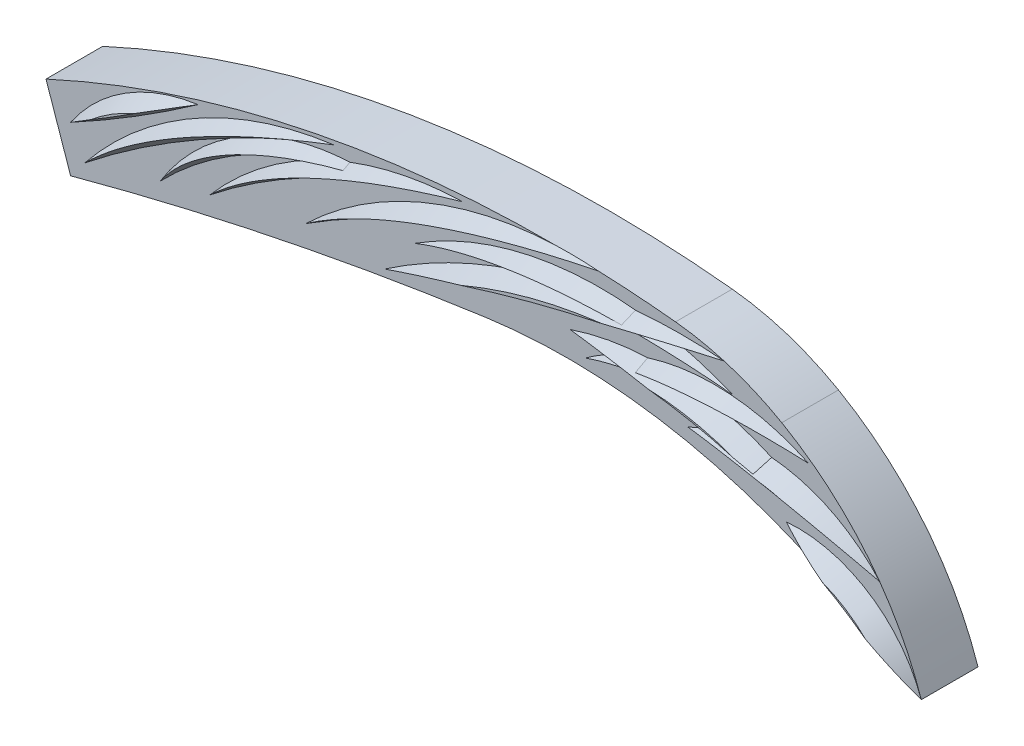
SolidWorks part; units mm, degrees
ref_plane "Plano frontal" through (0, 0, 0) normal (0, 0, 1) x (1, 0, 0)
ref_plane "Plano superior" through (0, 0, 0) normal (0, 1, 0) x (1, 0, 0)
ref_plane "Plano direito" through (0, 0, 0) normal (1, 0, 0) x (0, 0, -1)
sketch "Esboço4" plane through (0, 0, 0) normal (0, 0, 1) x (1, 0, 0)
  line L0 (0, 0) -> (-1.3028, 3.7819)
  arc A0 (-1.3028, 3.7819) -> (32, 9.3098) centre (25.4471, -54.2922) cw
  arc A1 (32, 9.3098) -> (37.6194, 7.5) centre (30.5413, -4.8482) cw
  arc A2 (45, -1.5) -> (22, 4.5) centre (26.2802, -26.176) ccw
  arc A3 (22, 4.5) -> (0, 0) centre (46.5941, -171.7657) ccw
  arc A4 (37.6194, 7.5) -> (45, -1.5) centre (29.4784, -6.7025) cw
  point P11 (29.4092, 8.7234)
  point P12 (34.2907, 7.7261)
  point P13 (25.5217, -13.5843)
  point P14 (23.8182, 4.8545)
  point P15 (0, 0)
  point P16 (34.6139, 7.3339)
  point P17 (21.2872, 5.0611)
  point P18 (22.1653, 4.4929)
  point P19 (26.8658, 8.8835)
  point P21 (28.2156, 8.9352)
  point P22 (34.0974, 9.1934)
  point P23 (30.2233, 9.71)
  point P24 (32.2034, 8.9868)
  point P25 (0, 0)
  point P26 (37.9197, 7.4372)
  point P27 (32, 9.3098)
  dimension "D9" = 63.9386
  dimension "D10" = 177.9732
  dimension "D11" = 14.233
  dimension "D12" = 16.3702
  dimension "D1" = 45
  dimension "D2" = 4
  dimension "D3" = 1.5
  dimension "D4" = 4.5
  dimension "D5" = 7.5
  dimension "D6" = 9.3098
  dimension "D7" = 22
  dimension "D8" = 32
extrude "Ressalto-extrusão2" add sketch "Esboço4" along normal blind 3
sketch "Esboço5" plane through (0, 0, 3) normal (0, 0, 1) x (1, 0, 0)
  arc A0 (0, 2.4508) -> (6.7381, 6.6316) centre (13.2084, -11.3167) cw
  arc A1 (0.7461, 0.9643) -> (13.9315, 8.3798) centre (20.9726, -19.5698) cw
  arc A2 (7.3646, 2.8065) -> (20.7523, 9.1823) centre (23.619, -14.0807) cw
  arc A3 (12.444, 4.0347) -> (27.9188, 9.5987) centre (29.3908, -18.7968) cw
  arc A4 (4.7377, 2.1242) -> (16.6099, 7.958) centre (16.2768, -6.3616) cw
  arc A5 (16.6099, 4.0347) -> (34.58, 8.7997) centre (36.2409, -33.7309) cw
  arc A6 (18.2133, 6.0134) -> (35.0324, 7.4803) centre (28.4248, -13.9131) cw
  arc A7 (27.2199, 5.2628) -> (39.0368, 6.345) centre (34.4616, -8.7549) cw
  arc A8 (32.6443, 4.8193) -> (42.8038, 2.8065) centre (35.7795, -6.0018) cw
  arc A9 (37.864, 3.0794) -> (45, -1.5) centre (36.488, -6.9145) cw
  arc A10 (32, 9.3098) -> (-1.3028, 3.7819) centre (25.4471, -54.2922) ccw construction
  arc A11 (37.6194, 7.5) -> (32, 9.3098) centre (30.5413, -4.8482) ccw construction
  arc A12 (45, -1.5) -> (37.6194, 7.5) centre (29.4784, -6.7025) ccw construction
  point P30 (6.7381, 6.6316)
  point P31 (13.9315, 8.3798)
  point P32 (20.7523, 9.1823)
  point P33 (27.9188, 9.5987)
  point P37 (34.58, 8.7997)
  point P41 (39.0368, 6.345)
  point P42 (42.8038, 2.8065)
  point P46 (45, -1.5)
sketch "Esboço6" plane through (0, 0, 3) normal (0, 0, 1) x (1, 0, 0)
  arc A0 (0, 2.4508) -> (6.7381, 6.6316) centre (8.079, -3.0498) cw
  arc A1 (0, 2.4508) -> (6.7381, 6.6316) centre (-31.6061, 60.9098) ccw
  arc A2 (6.7381, 6.6316) -> (0, 2.4508) centre (13.2084, -11.3167) ccw construction
  dimension "D1" = 9.729
  dimension "D2" = 85
extrude "Ressalto-extrusão5" add sketch "Esboço6" along normal blind 1 draft 23
sketch "Esboço7" plane through (0, 0, 3) normal (0, 0, 1) x (1, 0, 0)
  arc A0 (0.7461, 0.9643) -> (13.9315, 8.3798) centre (16.5557, -11.7163) cw
  arc A1 (0.7461, 0.9643) -> (13.9315, 8.3798) centre (30.5272, -36.5584) cw
  arc A2 (13.9315, 8.3798) -> (0.7461, 0.9643) centre (20.9726, -19.5698) ccw construction
  dimension "D1" = 19.4911
  dimension "D2" = 9.0104
extrude "Ressalto-extrusão6" add sketch "Esboço7" along normal blind 1 draft 28
sketch "Esboço8" plane through (0, 0, 3) normal (0, 0, 1) x (1, 0, 0)
  arc A0 (4.7377, 2.1242) -> (16.6099, 7.958) centre (15.3314, -4.4376) cw
  arc A1 (4.7377, 2.1242) -> (16.6099, 7.958) centre (18.7958, -11.4879) cw
  arc A2 (16.6099, 7.958) -> (4.7377, 2.1242) centre (16.2768, -6.3616) ccw construction
  dimension "D1" = 5.7117
  dimension "D2" = 2.1437
extrude "Ressalto-extrusão7" add sketch "Esboço8" along normal blind 1 draft 23
sketch "Esboço9" plane through (0, 0, 3) normal (0, 0, 1) x (1, 0, 0)
  arc A0 (7.3646, 2.8065) -> (20.7523, 9.1823) centre (21.2176, -9.0384) cw
  arc A1 (7.3646, 2.8065) -> (20.7523, 9.1823) centre (27.8279, -22.9185) cw
extrude "Ressalto-extrusão8" add sketch "Esboço9" along normal blind 1 draft 23
sketch "Esboço10" plane through (0, 0, 3) normal (0, 0, 1) x (1, 0, 0)
  arc A0 (12.444, 4.0347) -> (27.9188, 9.5987) centre (26.3952, -10.4653) cw
  arc A1 (12.444, 4.0347) -> (27.9188, 9.5987) centre (32.2566, -26.7672) cw
extrude "Ressalto-extrusão9" add sketch "Esboço10" along normal blind 1 draft 23
sketch "Esboço11" plane through (0, 0, 3) normal (0, 0, 1) x (1, 0, 0)
  arc A0 (18.2133, 6.0134) -> (35.0324, 7.4803) centre (28.0247, -9.3255) cw
  arc A1 (18.2133, 6.0134) -> (35.0324, 7.4803) centre (28.8862, -19.2022) cw
extrude "Ressalto-extrusão10" add sketch "Esboço11" along normal blind 1 draft 23
sketch "Esboço12" plane through (0, 0, 3) normal (0, 0, 1) x (1, 0, 0)
  arc A0 (16.6099, 4.0347) -> (34.58, 8.7997) centre (32.3026, -18.8789) cw
  arc A1 (16.6099, 4.0347) -> (34.58, 8.7997) centre (44.6841, -65.5719) cw
extrude "Ressalto-extrusão11" add sketch "Esboço12" along normal blind 1 draft 23
sketch "Esboço13" plane through (0, 0, 3) normal (0, 0, 1) x (1, 0, 0)
  arc A0 (27.2199, 5.2628) -> (39.0368, 6.345) centre (34.042, -4.1731) cw
  arc A1 (27.2199, 5.2628) -> (39.0368, 6.345) centre (34.8641, -13.1497) cw
extrude "Ressalto-extrusão12" add sketch "Esboço13" along normal blind 1 draft 23
sketch "Esboço14" plane through (0, 0, 3) normal (0, 0, 1) x (1, 0, 0)
  arc A0 (32.6443, 4.8193) -> (42.8038, 2.8065) centre (36.3816, -2.9628) cw
  arc A1 (32.6443, 4.8193) -> (42.8038, 2.8065) centre (34.8021, -10.9349) cw
extrude "Ressalto-extrusão13" add sketch "Esboço14" along normal blind 1 draft 23
sketch "Esboço15" plane through (0, 0, 3) normal (0, 0, 1) x (1, 0, 0)
  arc A0 (37.864, 3.0794) -> (45, -1.5) centre (38.4672, -3.8302) cw
  arc A1 (37.864, 3.0794) -> (45, -1.5) centre (31.9205, -14.0318) cw
  point P7 (45.0496, -1.5)
extrude "Ressalto-extrusão14" add sketch "Esboço15" along normal blind 1 draft 23
sketch "Esboço16" plane through (0, 0, 3) normal (0, 0, 1) x (1, 0, 0)
  arc A0 (26.4167, 6.1697) -> (40.6887, 3.3153) centre (31.0825, -7.6082) cw
  arc A1 (26.4167, 6.1697) -> (40.6887, 3.3153) centre (28.5082, -20.4799) cw
extrude "Ressalto-extrusão15" add sketch "Esboço16" along normal blind 1 draft 23
